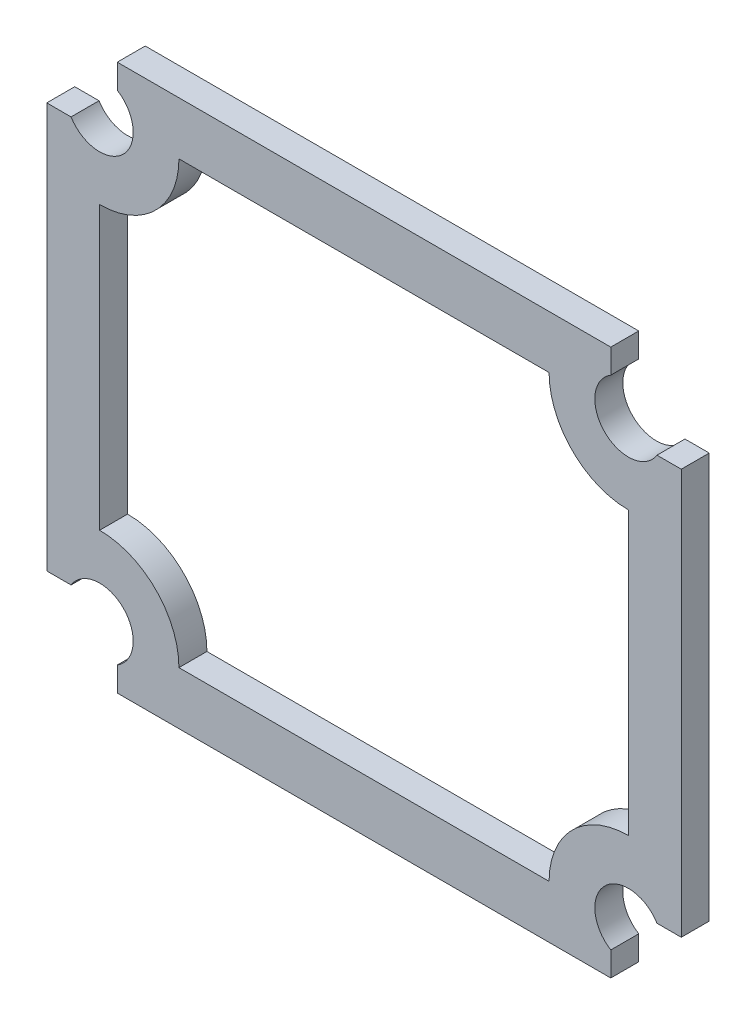
SolidWorks part; units mm, degrees
material "BUTYL"
ref_plane "Front Plane" through (0, 0, 0) normal (0, 0, 1) x (1, 0, 0)
ref_plane "Top Plane" through (0, 0, 0) normal (0, 1, 0) x (1, 0, 0)
ref_plane "Right Plane" through (0, 0, 0) normal (1, 0, 0) x (0, 0, -1)
sketch "Sketch1" plane through (0, 0, 0) normal (0, 0, 1) x (1, 0, 0)
  line L1 (-20, 0) -> (20, 0) construction
  line L2 (-20, 17.5) -> (20, 17.5) construction
  line L3 (-20, 17.5) -> (-20, -17.5) construction
  line L4 (-20, -17.5) -> (20, -17.5) construction
  line L5 (20, 17.5) -> (20, -17.5) construction
  line L6 (-20, 17.5) -> (20, -17.5) construction
  line L7 (-20, -17.5) -> (20, 17.5) construction
  line L8 (0, 17.5) -> (0, -17.5) construction
  line L12 (-18, 11.5) -> (-18, -11.5)
  line L13 (-18, -11.5) -> (-16.6214, -11.5)
  line L14 (14, -15.5) -> (-14, -15.5)
  line L15 (-14, -15.5) -> (-14, -14.1214)
  line L16 (-15, 8) -> (-15, -8)
  line L17 (10.5, -12.5) -> (-10.5, -12.5)
  line L20 (15, 8) -> (15, -8)
  line L21 (14, -15.5) -> (14, -14.1214)
  line L22 (18, -11.5) -> (16.6214, -11.5)
  line L23 (18, 11.5) -> (18, -11.5)
  line L24 (18, 11.5) -> (16.6214, 11.5)
  line L25 (14, 15.5) -> (14, 14.1214)
  line L26 (10.5, 12.5) -> (-10.5, 12.5)
  line L27 (-14, 15.5) -> (-14, 14.1214)
  line L28 (14, 15.5) -> (-14, 15.5)
  line L29 (-18, 11.5) -> (-16.6214, 11.5)
  arc A4 (-16.6214, -11.5) -> (-14, -14.1214) centre (-15, -12.5) cw
  arc A5 (-10.5, -12.5) -> (-15, -8) centre (-15, -12.5) ccw
  arc A6 (10.5, -12.5) -> (15, -8) centre (15, -12.5) cw
  arc A7 (16.6214, -11.5) -> (14, -14.1214) centre (15, -12.5) ccw
  arc A8 (16.6214, 11.5) -> (14, 14.1214) centre (15, 12.5) cw
  arc A9 (10.5, 12.5) -> (15, 8) centre (15, 12.5) ccw
  arc A10 (-10.5, 12.5) -> (-15, 8) centre (-15, 12.5) cw
  arc A11 (-16.6214, 11.5) -> (-14, 14.1214) centre (-15, 12.5) ccw
  point P0 (0, 15.5)
  point P7 (-15, 0)
  point P24 (0, -12.5)
  point P26 (0, -15.5)
  point P39 (18, 0)
  point P40 (15, 0)
  point P42 (-18, 0)
  point P43 (0, 12.5)
  dimension "D5" = 1.905
  dimension "D11" = 4.5
  dimension "D1" = 40
  dimension "D2" = 35
  dimension "D3" = 5
  dimension "D4" = 5
  dimension "D6" = 2
  dimension "D7" = 2
  dimension "D8" = 6
  dimension "D9" = 6
  dimension "D10" = 3
  dimension "D12" = 3
extrude "Boss-Extrude1" add sketch "Sketch1" along normal blind 1.5875
